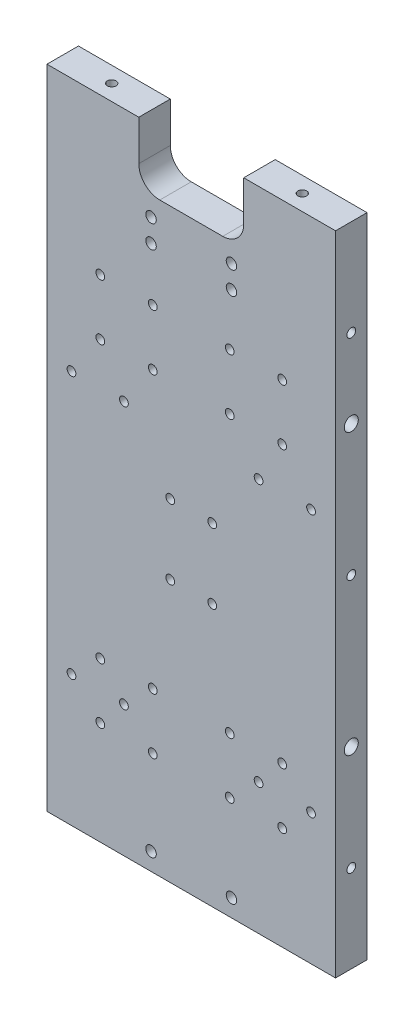
SolidWorks part; units mm, degrees
ref_plane "Front Plane" through (0, 0, 0) normal (0, 0, 1) x (1, 0, 0)
ref_plane "Top Plane" through (0, 0, 0) normal (0, 1, 0) x (1, 0, 0)
ref_plane "Right Plane" through (0, 0, 0) normal (1, 0, 0) x (0, 0, -1)
sketch "Sketch1" plane through (0, 0, 0) normal (0, 0, 1) x (1, 0, 0)
  line L1 (-82.5, 175) -> (82.5, 175)
  line L2 (-82.5, 175) -> (-82.5, -175)
  line L3 (-82.5, -175) -> (82.5, -175)
  line L4 (82.5, 175) -> (82.5, -175)
  line L5 (-82.5, 175) -> (82.5, -175) construction
  line L6 (-82.5, -175) -> (82.5, 175) construction
  point P0 (0, 0)
  dimension "D1" = 350
  dimension "D2" = 165
extrude "Boss-Extrude1" add sketch "Sketch1" along normal blind 18
hole_wizard "Ø6.0 (6) Diameter Hole1" positions "Sketch5" profile "Sketch4" hole size "Ø6.0" standard "ISO" end condition through all
sketch "Sketch5" plane through (0, 0, 18) normal (0, 0, 1) x (1, 0, 0)
  point P0 (-23, 149)
  point P3 (-23, 136)
  point P6 (23, 149)
  point P9 (23, 136)
sketch "Sketch4" plane through (-23, 149, 18) normal (1, 0, 0) x (0, -1, 0)
  line L0 (0, 0) -> (0, 18)
  line L1 (0, 18) -> (3, 18)
  line L2 (3, 18) -> (3, 0)
  line L5 (3, 0) -> (0, 0)
  line L11 (0, -6.35) -> (0, 107.95) construction
  dimension "Thru Hole Dia." = 6
  dimension "Thru Hole Depth" = 18
hole_wizard "Ø6.0 (6) Diameter Hole2" positions "Sketch7" profile "Sketch6" hole size "Ø6.0" standard "ISO" end condition through all
sketch "Sketch7" plane through (0, 0, 18) normal (0, 0, 1) x (1, 0, 0)
  point P0 (23, -165)
  point P3 (-23, -165)
sketch "Sketch6" plane through (23, -165, 18) normal (1, 0, 0) x (0, -1, 0)
  line L0 (0, 0) -> (0, 18)
  line L1 (0, 18) -> (3, 18)
  line L2 (3, 18) -> (3, 0)
  line L5 (3, 0) -> (0, 0)
  line L11 (0, -6.35) -> (0, 107.95) construction
  dimension "Thru Hole Dia." = 6
  dimension "Thru Hole Depth" = 18
hole_wizard "Otwór Ø5.0 (5)1" positions "Szkic2" profile "Szkic1" hole size "Ø5.0" standard "ISO" end condition through all
sketch "Szkic2" plane through (0, 0, 18) normal (0, 0, 1) x (1, 0, 0)
  point P0 (-68.5, 50)
  point P3 (-38.5, 50)
  point P6 (-68.5, -100)
  point P9 (-38.5, -100)
  point P12 (68.5, 50)
  point P15 (38.5, 50)
  point P18 (68.5, -100)
  point P21 (38.5, -100)
sketch "Szkic1" plane through (-68.5, 50, 18) normal (1, 0, 0) x (0, -1, 0)
  line L0 (0, 0) -> (0, 18)
  line L1 (0, 18) -> (2.5, 18)
  line L2 (2.5, 18) -> (2.5, 0)
  line L5 (2.5, 0) -> (0, 0)
  line L11 (0, -6.35) -> (0, 107.95) construction
  dimension "Średnica otworu na wylot" = 5
  dimension "Głębokość otworu na wylot" = 18
sketch "Szkic4" plane through (0, 0, 18) normal (0, 0, 1) x (1, 0, 0)
  line L1 (82.5, 175) -> (-82.5, 175)
  line L2 (82.5, 175) -> (82.5, 195)
  line L3 (82.5, 195) -> (-82.5, 195)
  line L4 (-82.5, 175) -> (-82.5, 195)
  dimension "D1" = 20
extrude "Dodanie-wyciągnięcie3" add sketch "Szkic4" against normal blind 18
sketch "Szkic5" plane through (0, 0, 18) normal (0, 0, 1) x (1, 0, 0)
  line L0 (82.5, 195) -> (-82.5, 195) construction
  line L1 (-30, 195) -> (30, 195)
  line L2 (-30, 195) -> (-30, 172)
  line L3 (-18, 160) -> (18, 160)
  line L4 (30, 195) -> (30, 172)
  line L5 (-82.5, 195) -> (-82.5, -175) construction
  arc A0 (30, 172) -> (18, 160) centre (18, 172) cw
  arc A1 (-18, 160) -> (-30, 172) centre (-18, 172) cw
  point P10 (30, 160)
  dimension "D4" = 12
  dimension "D1" = 60
  dimension "D2" = 52.5
  dimension "D3" = 35
extrude "Wytnij-wyciągnięcie2" cut sketch "Szkic5" against normal blind 18 contours L2 A1 L3 A0 L4 L1
hole_wizard "Otwór Ø5.0 (5)2" positions "Szkic7" profile "Szkic6" hole size "Ø5.0" standard "ISO" end condition through all
sketch "Szkic7" plane through (0, 0, 0) normal (0, 0, -1) x (-1, 0, 0)
  point P0 (-52, 106)
  point P2 (-22, 106)
  point P4 (-52, 74)
  point P6 (-22, 74)
  point P8 (22, 106)
  point P10 (52, 106)
  point P12 (52, 74)
  point P14 (22, 74)
  point P16 (-12, 15)
  point P18 (12, 15)
  point P20 (12, -25)
  point P22 (-12, -25)
  point P24 (-52, -84)
  point P26 (-22, -84)
  point P28 (-52, -116)
  point P30 (-22, -116)
  point P32 (22, -84)
  point P34 (52, -84)
  point P36 (22, -116)
  point P38 (52, -116)
sketch "Szkic6" plane through (52, 106, 0) normal (1, 0, 0) x (0, 1, 0)
  line L0 (0, 0) -> (0, 18)
  line L1 (0, 18) -> (2.5, 18)
  line L2 (2.5, 18) -> (2.5, 0)
  line L5 (2.5, 0) -> (0, 0)
  line L11 (0, -6.35) -> (0, 107.95) construction
  dimension "Średnica otworu na wylot" = 5
  dimension "Głębokość otworu na wylot" = 18
ref_plane "Płaszczyzna1" through (0, 0, 0) normal (-1, 0, 0) x (0, 0, 1)
hole_wizard "Otwór Ø5.0 (5)3" positions "Szkic12" profile "Szkic11" hole size "Ø5.0" standard "ISO"
sketch "Szkic12" plane through (0, 195, 0) normal (0, 1, 0) x (1, 0, 0)
  point P0 (-54.5, -9)
  point P2 (54.5, -9)
sketch "Szkic11" plane through (-54.5, 195, 9) normal (1, 0, 0) x (0, 0, 1)
  line L0 (0, 0) -> (0, 46.5022)
  line L1 (0, 46.5022) -> (2.5, 45)
  line L2 (2.5, 45) -> (2.5, 0)
  line L5 (2.5, 0) -> (0, 0)
  line L10 (0, 46.5022) -> (-2.5, 45) construction
  line L11 (0, -6.35) -> (0, 107.95) construction
  dimension "Średnica otworu" = 5
  dimension "Głębokość otworu" = 45
  dimension "Kąt wiertła" = 118
hole_wizard "Otwór Ø5.0 (5)4" positions "Szkic14" profile "Szkic13" hole size "Ø5.0" standard "ISO"
sketch "Szkic14" plane through (82.5, 0, 0) normal (1, 0, 0) x (0, 0, -1)
  line L0 (-18, -175) -> (-18, 195) construction
  line L1 (0, 195) -> (-18, 195) construction
  line L2 (-18, -175) -> (0, -175) construction
  point P0 (-9, 140)
  point P2 (-9, 20)
  point P4 (-9, -125)
  dimension "D1" = 9
  dimension "D2" = 9
  dimension "D3" = 9
  dimension "D4" = 55
  dimension "D5" = 50
  dimension "D6" = 120
sketch "Szkic13" plane through (82.5, 140, 9) normal (0, 1, 0) x (0, 0, -1)
  line L0 (0, 0) -> (0, 46.5022)
  line L1 (0, 46.5022) -> (2.5, 45)
  line L2 (2.5, 45) -> (2.5, 0)
  line L5 (2.5, 0) -> (0, 0)
  line L10 (0, 46.5022) -> (-2.5, 45) construction
  line L11 (0, -6.35) -> (0, 107.95) construction
  dimension "Średnica otworu" = 5
  dimension "Głębokość otworu" = 45
  dimension "Kąt wiertła" = 118
mirror "Lustro1" about plane through (0, 0, 0) normal (-1, 0, 0) of "Otwór Ø5.0 (5)4"
hole_wizard "Otwór Ø8.0 (8)1" positions "Szkic16" profile "Szkic15" hole size "Ø8.0" standard "ISO"
sketch "Szkic16" plane through (-82.5, 0, 0) normal (-1, 0, 0) x (0, 0, 1)
  line L0 (0, 195) -> (0, -175) construction
  line L1 (0, 195) -> (18, 195) construction
  line L2 (18, -175) -> (0, -175) construction
  point P0 (9, 95)
  point P2 (9, -65)
  dimension "D1" = 9
  dimension "D2" = 9
  dimension "D3" = 100
  dimension "D4" = 110
sketch "Szkic15" plane through (-82.5, 95, 9) normal (0, 1, 0) x (0, 0, 1)
  line L0 (0, 0) -> (0, 24.4034)
  line L1 (0, 24.4034) -> (4, 22)
  line L2 (4, 22) -> (4, 0)
  line L5 (4, 0) -> (0, 0)
  line L10 (0, 24.4034) -> (-4, 22) construction
  line L11 (0, -6.35) -> (0, 107.95) construction
  dimension "Średnica otworu" = 8
  dimension "Głębokość otworu" = 22
  dimension "Kąt wiertła" = 118
mirror "Lustro2" about plane through (0, 0, 0) normal (-1, 0, 0) of "Otwór Ø8.0 (8)1"
